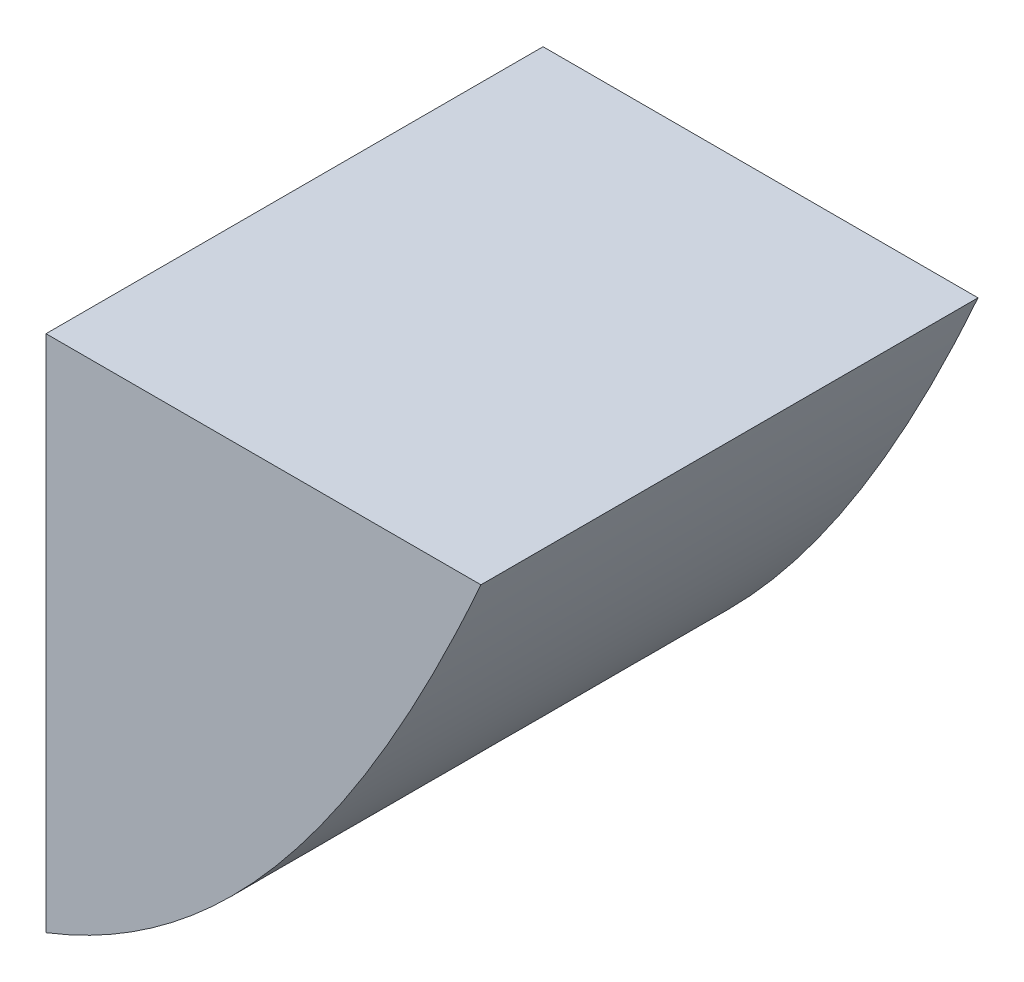
SolidWorks part; units mm, degrees
ref_plane "Front Plane" through (0, 0, 0) normal (0, 0, 1) x (1, 0, 0)
ref_plane "Top Plane" through (0, 0, 0) normal (0, 1, 0) x (1, 0, 0)
ref_plane "Right Plane" through (0, 0, 0) normal (1, 0, 0) x (0, 0, -1)
ref_plane "plane:profile" through (0, 0, 0) normal (0, 0, 1) x (1, 0, 0)
sketch "profile:cubic" plane through (0, 0, 0) normal (0, 0, 1) x (1, 0, 0)
  line L0 (12, 9) -> (0, 9)
  line L1 (0, 9) -> (0, 0)
  spline S0 degree 3 poles (0, 0) (4, 0) (8, 0) (12, 9) knots 0 0 0 0 1 1 1 1
extrude "feature:prism" add sketch "profile:cubic" along normal blind 8 separate body
sketch "profile:cut" plane through (0, 0, 0) normal (0, 0, 1) x (1, 0, 0)
  line L0 (-2, -2) -> (5, -2)
  line L1 (5, -2) -> (5, 11)
  line L2 (5, 11) -> (-2, 11)
  line L3 (-2, 11) -> (-2, -2)
extrude "feature:trim" cut sketch "profile:cut" along normal through all
